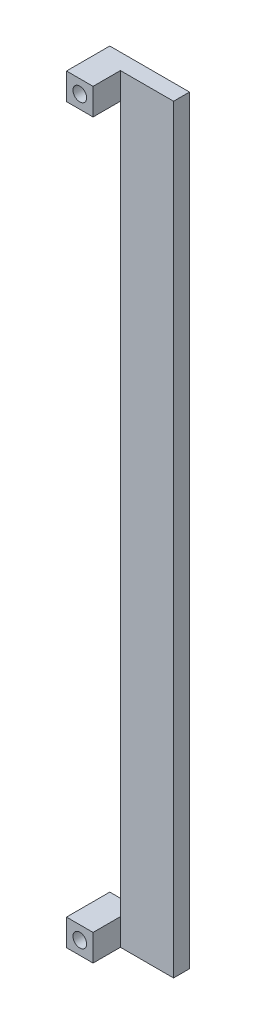
SolidWorks part; units mm, degrees
ref_plane "Спереди" through (0, 0, 0) normal (0, 0, 1) x (1, 0, 0)
ref_plane "Сверху" through (0, 0, 0) normal (0, 1, 0) x (1, 0, 0)
ref_plane "Справа" through (0, 0, 0) normal (1, 0, 0) x (0, 0, -1)
sketch "Эскиз1" plane through (0, 0, 0) normal (0, 0, 1) x (1, 0, 0)
  line L0 (-6.7032, 187.8725) -> (7.2968, 187.8725)
  line L1 (7.2968, 187.8725) -> (7.2968, -12.1275)
  line L2 (7.2968, -12.1275) -> (-6.7032, -12.1275)
  line L3 (-6.7032, -12.1275) -> (-6.7032, 187.8725)
  dimension "D1" = 14
  dimension "D2" = 200
extrude "Бобышка-Вытянуть1" add sketch "Эскиз1" along normal blind 4.2
sketch "Эскиз4" plane through (0, 0, 0) normal (0, 0, 1) x (1, 0, 0)
  line L1 (-6.7032, -12.1275) -> (-13.7032, -12.1275)
  line L2 (-6.7032, -12.1275) -> (-6.7032, -5.1275)
  line L3 (-6.7032, -5.1275) -> (-13.7032, -5.1275)
  line L4 (-13.7032, -12.1275) -> (-13.7032, -5.1275)
  line L5 (-6.7032, 187.8725) -> (-13.7032, 187.8725)
  line L6 (-6.7032, 187.8725) -> (-6.7032, 180.8725)
  line L7 (-6.7032, 180.8725) -> (-13.7032, 180.8725)
  line L8 (-13.7032, 187.8725) -> (-13.7032, 180.8725)
  circle A0 centre (-10.2032, -8.6275) radius 1.8
  circle A1 centre (-10.2032, 184.3725) radius 1.8
  dimension "D5" = 3.6
  dimension "D7" = 3.6
  dimension "D1" = 7
  dimension "D2" = 7
  dimension "D3" = 7
  dimension "D4" = 7
  dimension "D6" = 3.5
  dimension "D8" = 3.5
  dimension "D9" = 3.5
  dimension "D10" = 3.5
extrude "Бобышка-Вытянуть2" add sketch "Эскиз4" along normal blind 11.4
